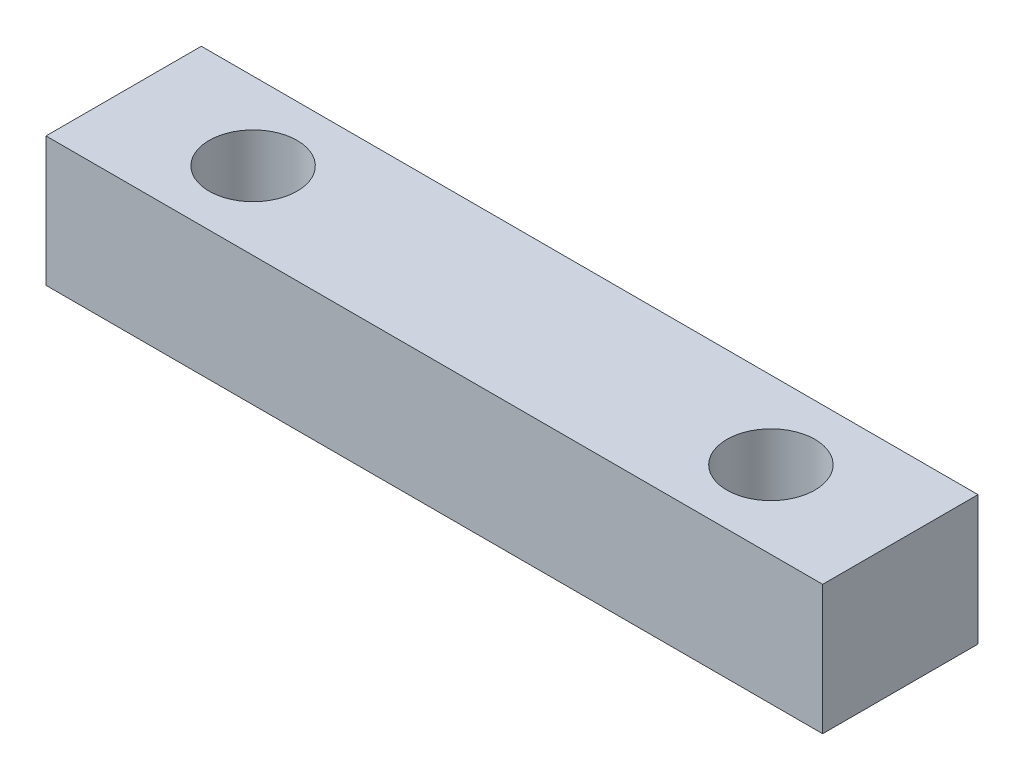
SolidWorks part; units mm, degrees
ref_plane "Plan de face" through (0, 0, 0) normal (0, 0, 1) x (1, 0, 0)
ref_plane "Plan de dessus" through (0, 0, 0) normal (0, 1, 0) x (1, 0, 0)
ref_plane "Plan de droite" through (0, 0, 0) normal (1, 0, 0) x (0, 0, -1)
sketch "Esquisse1" plane through (0, 0, 0) normal (0, 1, 0) x (1, 0, 0)
  line L1 (15, -3) -> (-15, -3)
  line L2 (15, -3) -> (15, 3)
  line L3 (15, 3) -> (-15, 3)
  line L4 (-15, -3) -> (-15, 3)
  line L5 (15, -3) -> (-15, 3) construction
  line L6 (15, 3) -> (-15, -3) construction
  point P0 (0, 0)
  dimension "D1" = 30
  dimension "D2" = 6
extrude "Boss.-Extru.1" add sketch "Esquisse1" along normal blind 5
sketch "Esquisse2" plane through (0, 0, 0) normal (0, -1, 0) x (1, 0, 0)
  line L0 (15, 0) -> (-15, 0) construction
  line L1 (15, 3) -> (15, -3) construction
  line L2 (-15, -3) -> (-15, 3) construction
  line L3 (10, 0) -> (10, 3) construction
  line L4 (-15, 3) -> (15, 3) construction
  line L5 (-10, 0) -> (-10, 3) construction
  dimension "D1" = 5
  dimension "D2" = 5
hole_wizard "Dégagement M31" positions "Esquisse4" profile "Esquisse3" hole size "M3" standard "ISO"
sketch "Esquisse4" plane through (0, 0, 0) normal (0, -1, 0) x (1, 0, 0)
  point P0 (10, 0)
  point P1 (-10, 0)
sketch "Esquisse3" plane through (10, 0, 0) normal (1, 0, 0) x (0, 0, -1)
  line L0 (0, 0) -> (0, 6.0215)
  line L1 (0, 6.0215) -> (1.7, 5)
  line L2 (1.7, 5) -> (1.7, 0)
  line L5 (1.7, 0) -> (0, 0)
  line L10 (0, 6.0215) -> (-1.7, 5) construction
  line L11 (0, -6.35) -> (0, 107.95) construction
  dimension "Diamètre du perçage" = 3.4
  dimension "Profondeur du perçage" = 5
  dimension "Angle de pointe" = 118
